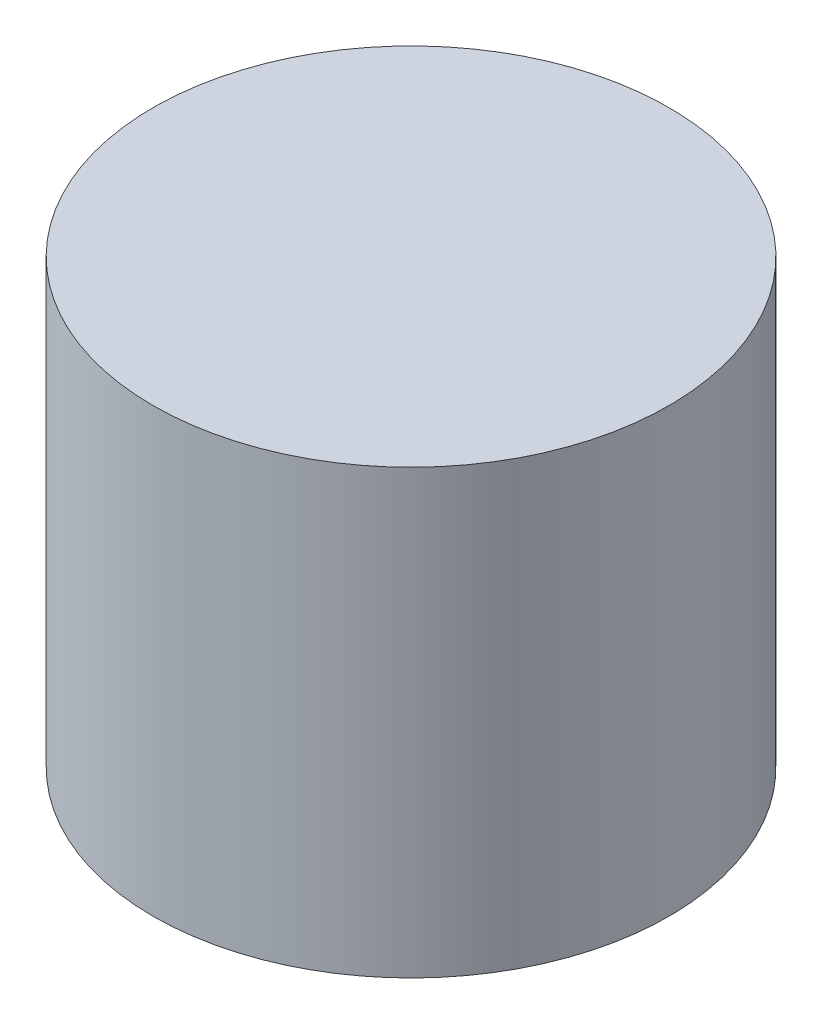
SolidWorks part; units mm, degrees
ref_plane "Front Plane" through (0, 0, 0) normal (0, 0, 1) x (1, 0, 0)
ref_plane "Top Plane" through (0, 0, 0) normal (0, 1, 0) x (1, 0, 0)
ref_plane "Right Plane" through (0, 0, 0) normal (1, 0, 0) x (0, 0, -1)
sketch "Sketch1" plane through (0, 0, 0) normal (0, 1, 0) x (1, 0, 0)
  circle A0 centre (0, 0) radius 3.5
  dimension "D1" = 7
extrude "Boss-Extrude1" add sketch "Sketch1" along normal blind 6
